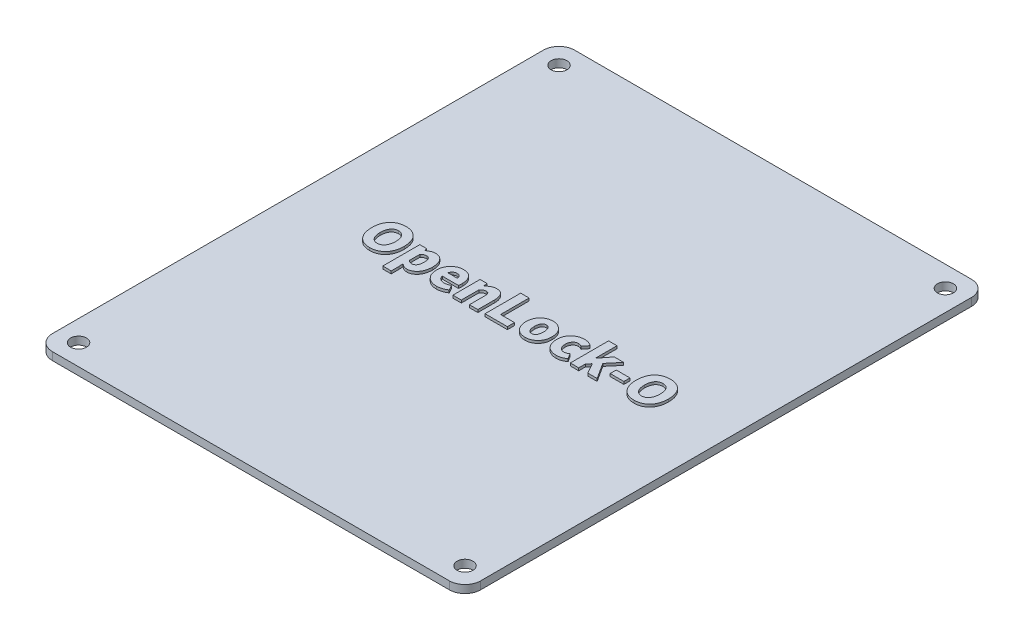
SolidWorks part; units mm, degrees
ref_plane "前视基准面" through (0, 0, 0) normal (0, 0, 1) x (1, 0, 0)
ref_plane "上视基准面" through (0, 0, 0) normal (0, 1, 0) x (1, 0, 0)
ref_plane "右视基准面" through (0, 0, 0) normal (1, 0, 0) x (0, 0, -1)
other "Configuration Table"
sketch "草图1" plane through (0, 0, 0) normal (0, 1, 0) x (1, 0, 0)
  line L1 (0, 0) -> (82, 0)
  line L2 (0, 0) -> (0, -100)
  line L3 (0, -100) -> (82, -100)
  line L4 (82, 0) -> (82, -100)
  circle A0 centre (78, -4) radius 1.525
  circle A1 centre (4, -4) radius 1.525
  circle A2 centre (4, -96) radius 1.525
  circle A3 centre (78, -96) radius 1.525
  point P15 (3.2126, -95.9063)
  dimension "D5" = 3.05
  dimension "D1" = 82
  dimension "D2" = 100
  dimension "D3" = 4
  dimension "D4" = 4
  dimension "D8" = 4
  dimension "D9" = 4
  dimension "D10" = 4
  dimension "D6" = 2
  dimension "D7" = 2
extrude "凸台-拉伸1" add sketch "草图1" along normal blind 1.5
sketch "草图2" plane through (0, 1.5, 0) normal (0, 1, 0) x (1, 0, 0)
  text T0 "OpenLock-O" font "思源黑体 Heavy" height in points 22
extrude "凸台-拉伸2" add sketch "草图2" along normal blind 0.5
fillet "圆角1" radius 3 4 edges at (0, 0.75, 100) (82, 0.75, 100) (82, 0.75, 0) (0, 0.75, 0)
